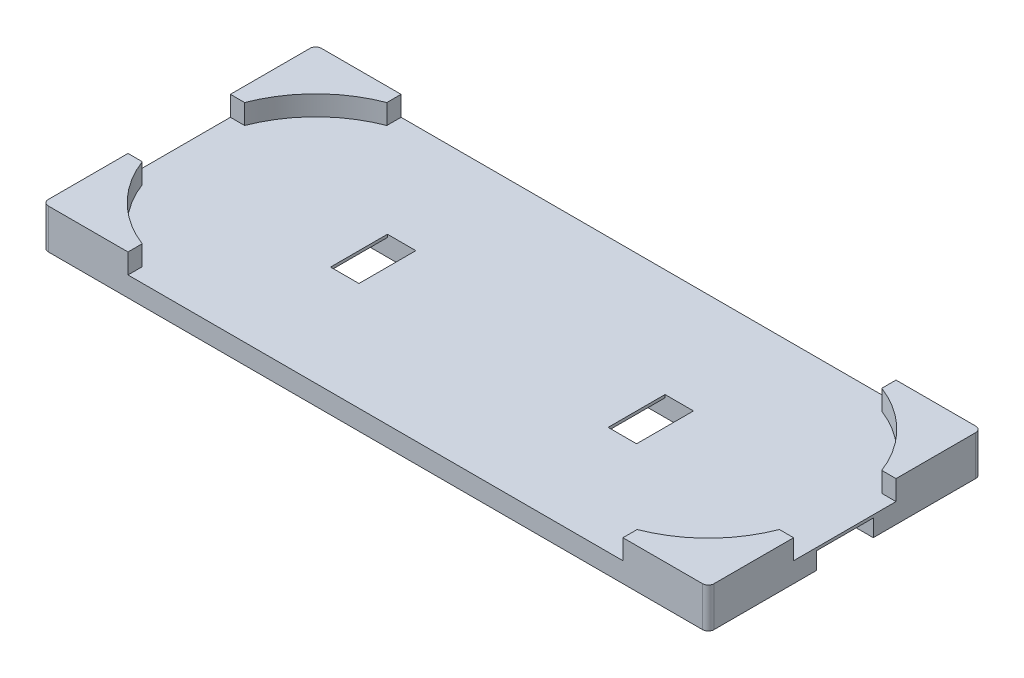
SolidWorks part; units mm, degrees
ref_plane "Front Plane" through (0, 0, 0) normal (0, 0, 1) x (1, 0, 0)
ref_plane "Top Plane" through (0, 0, 0) normal (0, 1, 0) x (1, 0, 0)
ref_plane "Right Plane" through (0, 0, 0) normal (1, 0, 0) x (0, 0, -1)
sketch "Sketch1" plane through (0, 0, 0) normal (0, 1, 0) x (1, 0, 0)
  line L1 (-5.85, 2.4) -> (5.85, 2.4)
  line L2 (-5.85, 2.4) -> (-5.85, -2.4)
  line L3 (-5.85, -2.4) -> (5.85, -2.4)
  line L4 (5.85, 2.4) -> (5.85, -2.4)
  line L5 (-5.85, 2.4) -> (5.85, -2.4) construction
  line L6 (-5.85, -2.4) -> (5.85, 2.4) construction
  point P0 (0, 0)
  dimension "D1" = 11.7
  dimension "D2" = 4.8
extrude "Boss-Extrude1" add sketch "Sketch1" along normal blind 0.35
sketch "Sketch2" plane through (0, 0, 0) normal (0, -1, 0) x (1, 0, 0)
  line L2 (-5.85, 0.5) -> (-5.85, -0.5)
  line L4 (5.85, 0.5) -> (5.85, -0.5)
  line L7 (-5.85, 0.5) -> (-1.85, 0.5)
  line L8 (5.85, 0.5) -> (1.85, 0.5)
  line L9 (-1.85, 0.5) -> (-1.85, -0.5)
  line L10 (1.85, 0.5) -> (1.85, -0.5)
  line L11 (-1.85, -0.5) -> (-5.85, -0.5)
  line L12 (1.85, -0.5) -> (5.85, -0.5)
  point P0 (0, 0)
  dimension "D3" = 4
  dimension "D4" = 1
extrude "Cut-Extrude2" cut sketch "Sketch2" against normal blind 0.3
sketch "Sketch4" plane through (0, 0.35, 0) normal (0, 1, 0) x (1, 0, 0)
  line L0 (0, 4.1035) -> (0, -3.5673) construction
  line L1 (-3.1279, 0) -> (2.2789, 0) construction
  line L2 (-4.35, 2.4) -> (-5.85, 2.4)
  line L3 (5.85, 2.4) -> (-5.85, 2.4) construction
  line L4 (4.35, 2.4) -> (4.35, 2.15)
  line L5 (-5.85, 2.4) -> (-5.85, 0.9)
  line L6 (-5.85, 2.4) -> (-5.85, -2.4) construction
  line L7 (5.85, 0.9) -> (5.6, 0.9)
  line L8 (-5.85, 0.9) -> (-5.6, 0.9)
  line L9 (5.85, 2.4) -> (5.85, 0.9)
  line L10 (-4.35, 2.4) -> (-4.35, 2.15)
  line L11 (4.35, 2.4) -> (4.35, 2.4213)
  line L12 (4.35, 2.4) -> (5.85, 2.4)
  line L13 (4.35, -2.4) -> (5.85, -2.4)
  line L14 (4.35, -2.4) -> (4.35, -2.4213)
  line L15 (5.85, -2.4) -> (5.85, -0.9)
  line L16 (5.85, -0.9) -> (5.6, -0.9)
  line L17 (4.35, -2.4) -> (4.35, -2.15)
  line L18 (-4.35, -2.4) -> (-4.35, -2.15)
  line L19 (-5.85, -0.9) -> (-5.6, -0.9)
  line L20 (-5.85, -2.4) -> (-5.85, -0.9)
  line L21 (-4.35, -2.4) -> (-5.85, -2.4)
  arc A0 (-5.6, 0.9) -> (-4.35, 2.15) centre (-3.5659, 0.1159) cw
  arc A1 (5.6, 0.9) -> (4.35, 2.15) centre (3.5659, 0.1159) ccw
  arc A2 (5.6, -0.9) -> (4.35, -2.15) centre (3.5659, -0.1159) cw
  arc A3 (-5.6, -0.9) -> (-4.35, -2.15) centre (-3.5659, -0.1159) ccw
  dimension "D5" = 2.18
  dimension "D1" = 1.5
  dimension "D2" = 1.5
  dimension "D3" = 0.25
  dimension "D4" = 0.25
extrude "Boss-Extrude3" add sketch "Sketch4" along normal blind 0.35 contours L16 A2 L17 L3 L0
fillet "Fillet2" radius 0.1 4 edges at (5.85, 0.35, -2.4) (5.85, 0.35, 2.4) (-5.85, 0.35, -2.4) (-5.85, 0.35, 2.4)
sketch "Sketch6" plane through (0, 0.3, 0) normal (0, -1, 0) x (1, 0, 0)
  line L0 (0, 3.0505) -> (0, -3.1101) construction
  line L1 (2.69, 0.5) -> (2.69, -0.5)
  line L2 (-2.69, 0.5) -> (-2.19, 0.5)
  line L3 (-2.69, 0.5) -> (-2.69, -0.5)
  line L4 (-2.69, -0.5) -> (-2.19, -0.5)
  line L5 (-2.19, 0.5) -> (-2.19, -0.5)
  line L6 (2.69, 0.5) -> (2.19, 0.5)
  line L7 (2.19, 0.5) -> (2.19, -0.5)
  line L8 (2.69, -0.5) -> (2.19, -0.5)
  line L9 (-1.85, 0.5) -> (-5.85, 0.5) construction
  line L10 (-1.85, -0.5) -> (-1.85, 0.5) construction
  dimension "D1" = 0.5
  dimension "D2" = 1
  dimension "D3" = 0.34
extrude "Cut-Extrude3" cut sketch "Sketch6" against normal blind 1
